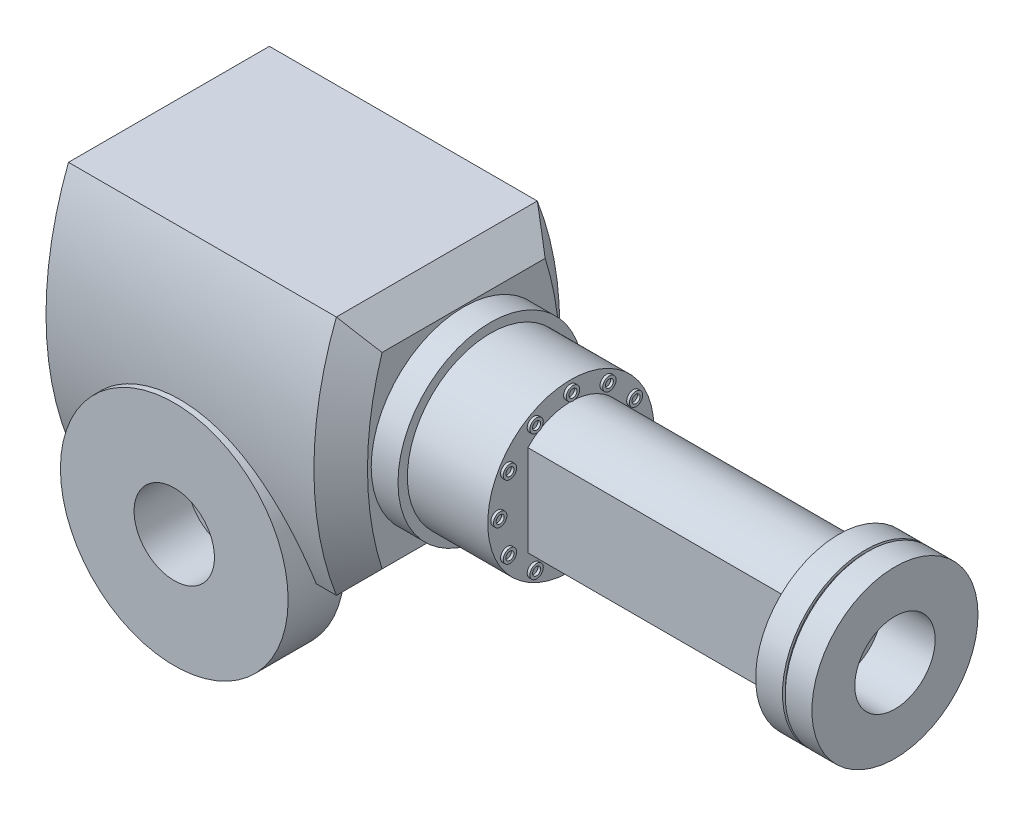
SolidWorks part; units mm, degrees
ref_plane "Front Plane" through (0, 0, 0) normal (0, 0, 1) x (1, 0, 0)
ref_plane "Top Plane" through (0, 0, 0) normal (0, 1, 0) x (1, 0, 0)
ref_plane "Right Plane" through (0, 0, 0) normal (1, 0, 0) x (0, 0, -1)
sketch "Sketch1" plane through (0, 0, 0) normal (1, 0, 0) x (0, 0, -1)
  line L0 (-48.3815, 0) -> (60, 0) construction
  line L1 (0, 51.2428) -> (0, -58.3526) construction
  line L2 (-37.5, 45) -> (37.5, 45)
  line L3 (37.5, -45) -> (-37.5, -45)
  arc A0 (37.5, 45) -> (37.5, -45) centre (-79.119, 0) cw
  arc A1 (-37.5, 45) -> (-37.5, -45) centre (79.119, 0) ccw
  point P11 (0, -45)
  point P13 (0, 45)
  dimension "D3" = 125
  dimension "D1" = 45
  dimension "D2" = 45
  dimension "D4" = 37.5
  dimension "D5" = 37.5
extrude "Boss-Extrude1" add sketch "Sketch1" along normal blind 100
sketch "Sketch2" plane through (100, 0, 0) normal (1, 0, 0) x (0, 0, -1)
  line L2 (37.5, 45) -> (-37.5, 45)
  line L3 (-37.5, -45) -> (37.5, -45)
  line L4 (37.5, 45) -> (-37.5, 45)
  line L5 (-37.5, -45) -> (37.5, -45)
  arc A2 (37.5, -45) -> (37.5, 45) centre (-79.119, 0) ccw
  arc A3 (-37.5, 45) -> (-37.5, -45) centre (79.119, 0) ccw
  arc A4 (37.5, -45) -> (37.5, 45) centre (-79.119, 0) ccw
  arc A5 (-37.5, 45) -> (-37.5, -45) centre (79.119, 0) ccw
  dimension "D1" = 0
extrude "Boss-Extrude2" add sketch "Sketch2" along normal blind 10 draft 45
sketch "Sketch4" plane through (110, 0, 0) normal (1, 0, 0) x (0, 0, -1)
  circle A0 centre (0, 0) radius 34.5
  dimension "D1" = 69
extrude "Boss-Extrude3" add sketch "Sketch4" along normal blind 10
sketch "Sketch5" plane through (120, 0, 0) normal (1, 0, 0) x (0, 0, -1)
  circle A0 centre (0, 0) radius 31
  dimension "D1" = 62
extrude "Boss-Extrude4" add sketch "Sketch5" along normal blind 30
sketch "Sketch6" plane through (150, 0, 0) normal (1, 0, 0) x (0, 0, -1)
  circle A0 centre (27, 0) radius 2.5
  circle A1 centre (27, 0) radius 1.5
  dimension "D2" = 5
  dimension "D3" = 1
  dimension "D1" = 27
extrude "Boss-Extrude5" add sketch "Sketch6" along normal blind 1
pattern_circular "CirPattern1" count 12 over 360 about axis through (0, 0, 0.1767) along (1, 0, 0) of "Boss-Extrude5"
sketch "Sketch7" plane through (150, 0, 0) normal (1, 0, 0) x (0, 0, -1)
  line L0 (-19.3079, 0) -> (15.7103, 0) construction
  line L1 (16, 17) -> (16, -17)
  line L2 (0, 14.8258) -> (0, -9.9031) construction
  line L3 (-16, 17) -> (-16, -17)
  arc A0 (-16, 17) -> (16, 17) centre (0, 1.9003) cw
  arc A1 (-16, -17) -> (16, -17) centre (0, -1.9003) ccw
  point P11 (-68.7705, 31.4474)
  dimension "D4" = 22
  dimension "D1" = 16
  dimension "D2" = 17
extrude "Boss-Extrude6" add sketch "Sketch7" along normal blind 100
sketch "Sketch8" plane through (250, 0, 0) normal (1, 0, 0) x (0, 0, -1)
  circle A0 centre (0, 0) radius 31
  dimension "D1" = 62
extrude "Boss-Extrude7" add sketch "Sketch8" along normal blind 10
sketch "Sketch9" plane through (260, 0, 0) normal (1, 0, 0) x (0, 0, -1)
  circle A0 centre (0, 0) radius 30
  circle A1 centre (0, 0) radius 31 construction
  dimension "D1" = 1
extrude "Boss-Extrude8" add sketch "Sketch9" along normal blind 1
sketch "Sketch10" plane through (261, 0, 0) normal (1, 0, 0) x (0, 0, -1)
  circle A0 centre (0, 0) radius 31
extrude "Boss-Extrude9" add sketch "Sketch10" along normal blind 10
ref_plane "Plane1" through (0, 0, 37.5) normal (0, 0, 1) x (1, 0, 0)
sketch "Sketch11" plane through (0, 0, 37.5) normal (0, 0, 1) x (1, 0, 0)
  line L0 (100, -45) -> (0, -45) construction
  circle A0 centre (50, -45) radius 42.5
  dimension "D1" = 85
extrude "Boss-Extrude10" add sketch "Sketch11" along normal mid plane 21
sketch "Sketch12" plane through (0, 0, 27) normal (0, 0, -1) x (-1, 0, 0)
  line L0 (-68.571, -45) -> (-28.571, -45)
  line L2 (-7.5, -45) -> (-92.5, -45) construction
  line L3 (-28.571, -45) -> (-28.571, -75)
  line L4 (-68.571, -45) -> (-68.571, -75)
  arc A0 (-68.571, -75) -> (-28.571, -75) centre (-48.571, -52.6393) ccw
  point P3 (-48.571, -45)
  dimension "D4" = 30
  dimension "D1" = 40
  dimension "D2" = 30
  dimension "D3" = 30
extrude "Boss-Extrude11" add sketch "Sketch12" along normal blind 35
sketch "Sketch13" plane through (68.571, 0, 0) normal (1, 0, 0) x (0, 0, -1)
  line L0 (8, -45) -> (8, -87)
  line L1 (8, -45) -> (33, -45)
  line L2 (-37.5, -45) -> (37.5, -45) construction
  arc A0 (33, -45) -> (8, -87) centre (-21.8393, -40.7981) cw
  dimension "D3" = 55
  dimension "D1" = 25
  dimension "D2" = 42
extrude "Boss-Extrude12" add sketch "Sketch13" against normal blind 40
sketch "Sketch14" plane through (0, 0, -8) normal (0, 0, 1) x (1, 0, 0)
  line L3 (28.571, -75) -> (28.571, -87)
  line L4 (28.571, -87) -> (68.571, -87)
  line L5 (68.571, -87) -> (68.571, -75)
  line L6 (28.571, -75) -> (28.571, -87)
  line L7 (28.571, -87) -> (68.571, -87)
  line L8 (68.571, -87) -> (68.571, -75)
  arc A1 (28.571, -75) -> (68.571, -75) centre (48.571, -52.6393) ccw
  arc A2 (28.571, -75) -> (68.571, -75) centre (48.571, -52.6393) ccw
  dimension "D1" = 0
extrude "Cut-Extrude1" cut sketch "Sketch14" against normal blind 40
sketch "Sketch15" plane through (271, 0, 0) normal (1, 0, 0) x (0, 0, -1)
  circle A0 centre (0, 0) radius 15
  dimension "D1" = 30
extrude "Cut-Extrude2" cut sketch "Sketch15" against normal blind 20
sketch "Sketch16" plane through (0, 0, 48) normal (0, 0, 1) x (1, 0, 0)
  circle A0 centre (50, -45) radius 15
  dimension "D1" = 30
extrude "Cut-Extrude3" cut sketch "Sketch16" against normal blind 20
